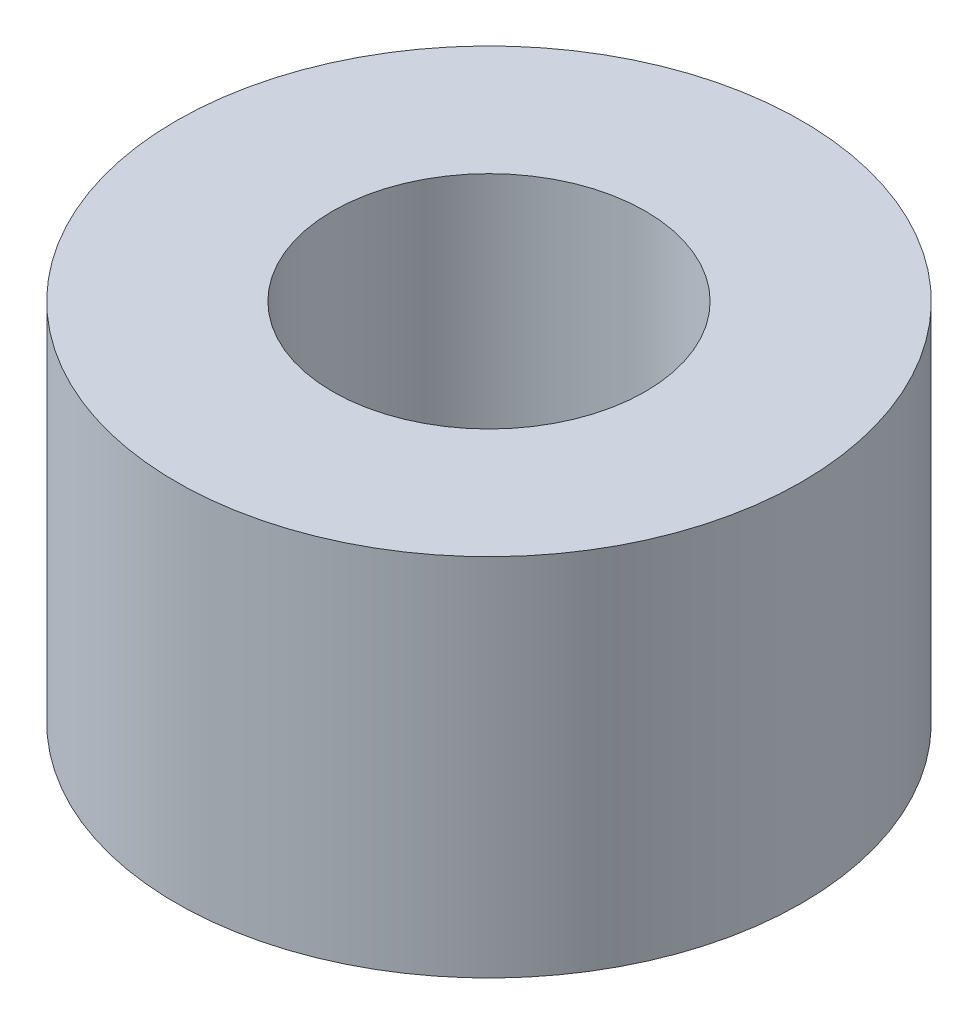
SolidWorks part; units mm, degrees
ref_plane "Front Plane" through (0, 0, 0) normal (0, 0, 1) x (1, 0, 0)
ref_plane "Top Plane" through (0, 0, 0) normal (0, 1, 0) x (1, 0, 0)
ref_plane "Right Plane" through (0, 0, 0) normal (1, 0, 0) x (0, 0, -1)
sketch "Sketch1" plane through (0, 0, 0) normal (0, 1, 0) x (1, 0, 0)
  circle A0 centre (0, 0) radius 3
  dimension "D1" = 6
extrude "Extrude-Thin1" add sketch "Sketch1" along normal blind 7 thin
